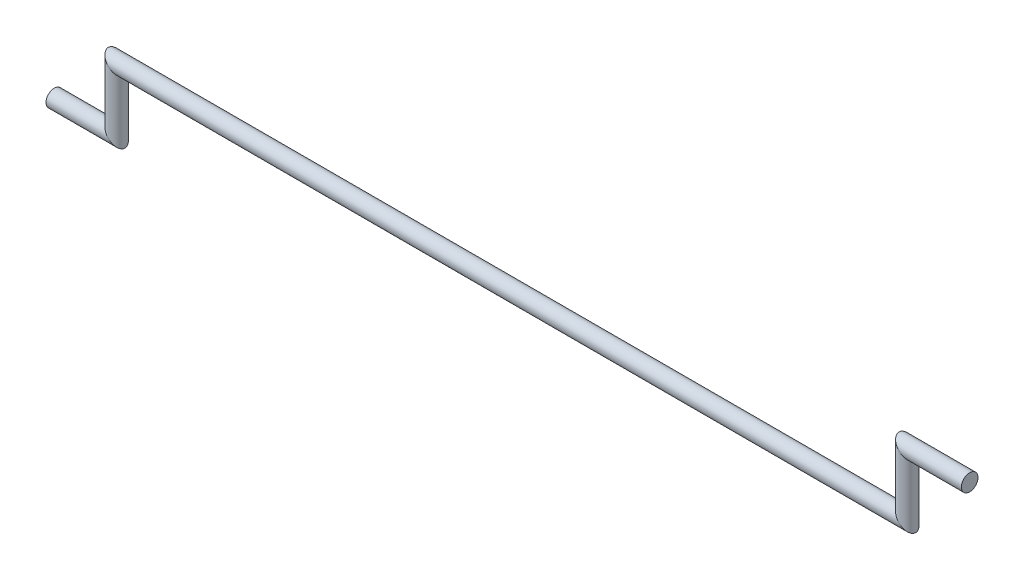
SolidWorks part; units mm, degrees
ref_plane "Front Plane" through (0, 0, 0) normal (0, 0, 1) x (1, 0, 0)
ref_plane "Top Plane" through (0, 0, 0) normal (0, 1, 0) x (1, 0, 0)
ref_plane "Right Plane" through (0, 0, 0) normal (1, 0, 0) x (0, 0, -1)
sketch "Sketch2" plane through (0, 0, 0) normal (0, 0, 1) x (1, 0, 0)
  line L0 (0, 0) -> (3, 0)
  line L1 (3, 0) -> (3, 3)
  line L2 (3, 3) -> (41.05, 3)
  line L3 (41.05, 3) -> (41.05, 6)
  line L4 (41.05, 6) -> (44.05, 6)
  dimension "D1" = 3
  dimension "D2" = 3
  dimension "D3" = 38.05
  dimension "D4" = 3
  dimension "D5" = 3
sketch "Sketch3" plane through (0, 0, 0) normal (1, 0, 0) x (0, 0, -1)
  circle A0 centre (0, 0) radius 0.4
  dimension "D1" = 0.8
sweep "Sweep1" add profiles "Sketch3" path "Sketch2"
